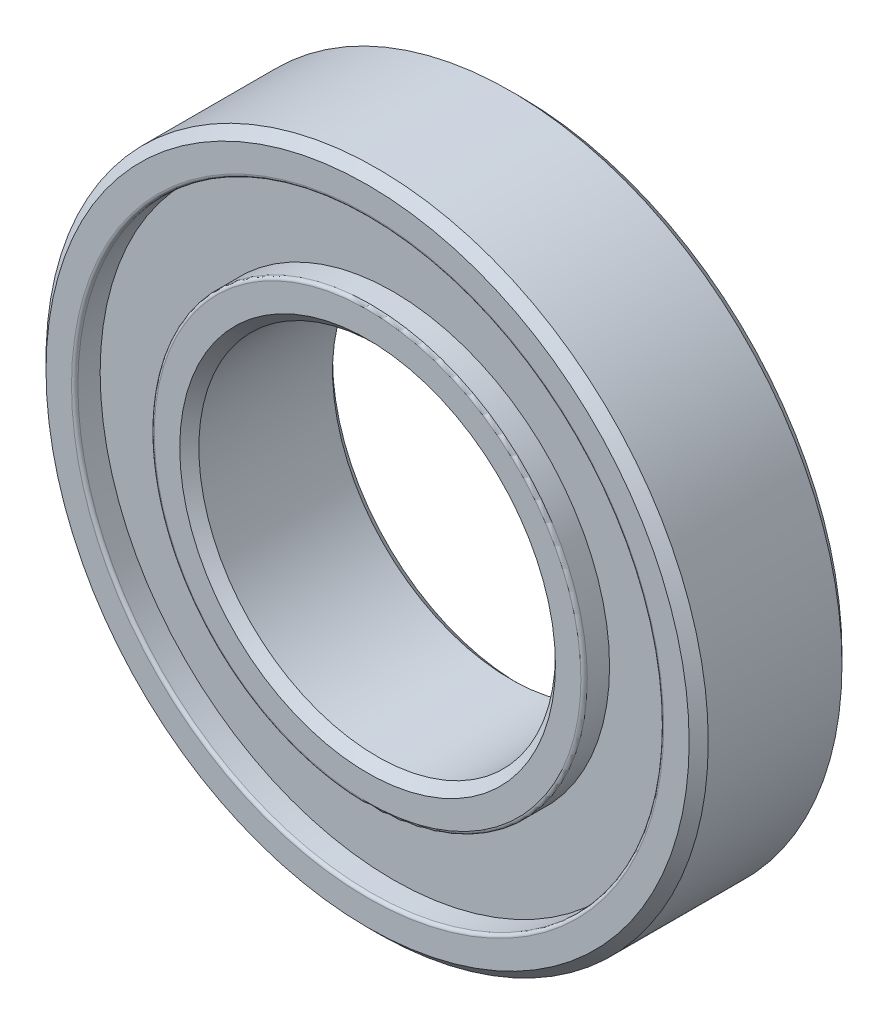
SolidWorks part; units mm, degrees
ref_plane "前视基准面" through (0, 0, 0) normal (0, 0, 1) x (1, 0, 0)
ref_plane "上视基准面" through (0, 0, 0) normal (0, 1, 0) x (1, 0, 0)
ref_plane "右视基准面" through (0, 0, 0) normal (1, 0, 0) x (0, 0, -1)
other "Configuration Table"
sketch "草图1" plane through (0, 0, 0) normal (0, 0, 1) x (1, 0, 0)
  circle A0 centre (0, 0) radius 26
  circle A1 centre (0, 0) radius 14
  dimension "D1" = 52
  dimension "D2" = 28
extrude "凸台-拉伸1" add sketch "草图1" along normal mid plane 12
sketch "草图2" plane through (0, 0, 6) normal (0, 0, 1) x (1, 0, 0)
  circle A0 centre (0, 0) radius 17
  circle A1 centre (0, 0) radius 23
  dimension "D1" = 46
  dimension "D2" = 34
extrude "切除-拉伸1" cut sketch "草图2" against normal blind 2 contours A1 A0
mirror "镜向1" about plane through (0, 0, 0) normal (0, 0, 1) of "切除-拉伸1"
chamfer "倒角1" distance 0.75 angle 45 4 edges at (14, 0, -6) (26, 0, -6) (14, 0, 6) (26, 0, 6)
fillet "圆角1" radius 0.25 4 edges at (17, 0, 6) (23, 0, 6) (23, 0, -6) (17, 0, -6)
